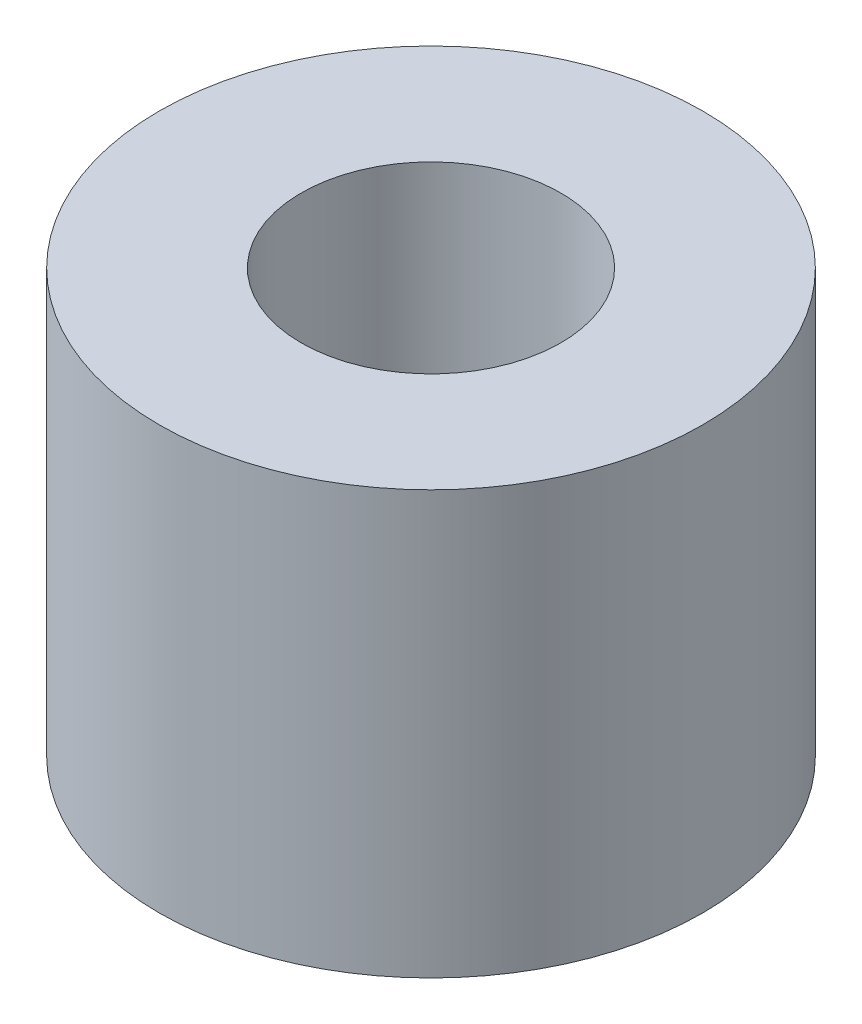
SolidWorks part; units mm, degrees
ref_plane "Спереди" through (0, 0, 0) normal (0, 0, 1) x (1, 0, 0)
ref_plane "Сверху" through (0, 0, 0) normal (0, 1, 0) x (1, 0, 0)
ref_plane "Справа" through (0, 0, 0) normal (1, 0, 0) x (0, 0, -1)
sketch "Эскиз1" plane through (0, 0, 0) normal (0, 1, 0) x (1, 0, 0)
  circle A0 centre (0, 0) radius 4.5
  circle A1 centre (0, 0) radius 2.15
  dimension "D1" = 4.3
  dimension "D2" = 9
extrude "Бобышка-Вытянуть1" add sketch "Эскиз1" along normal blind 7
